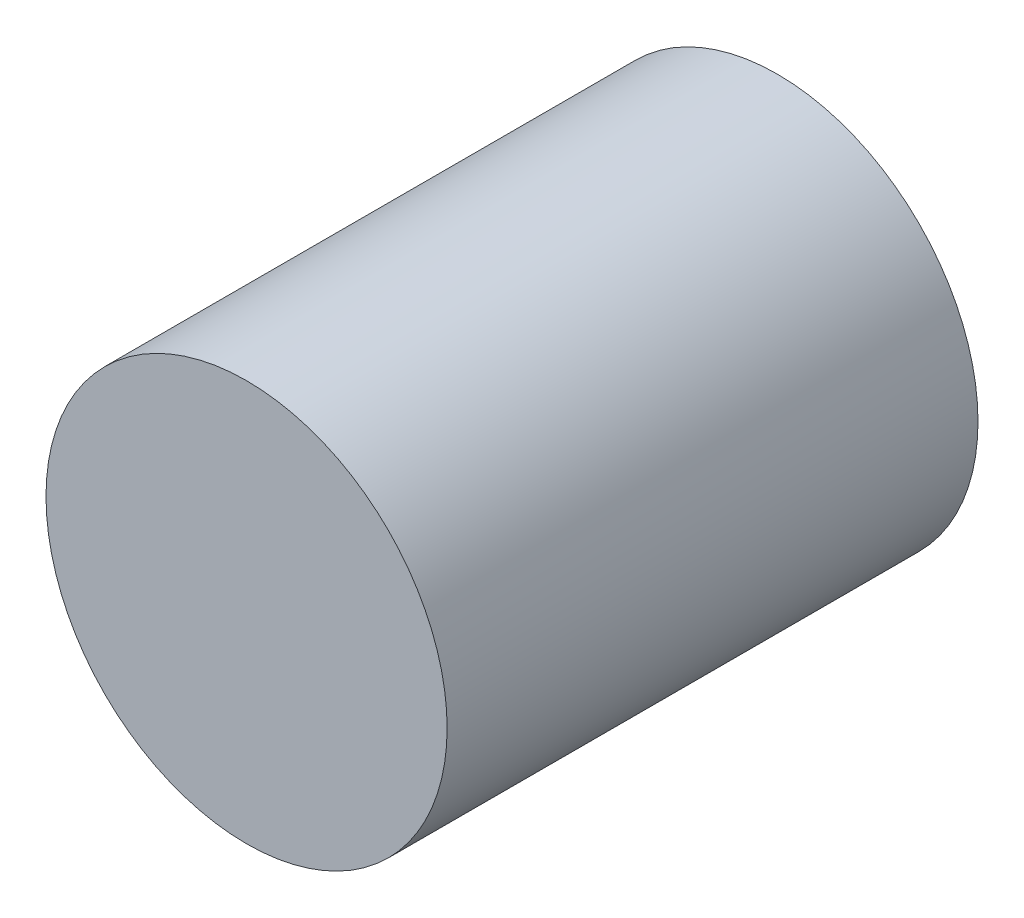
SolidWorks part; units mm, degrees
ref_plane "Front Plane" through (0, 0, 0) normal (0, 0, 1) x (1, 0, 0)
ref_plane "Top Plane" through (0, 0, 0) normal (0, 1, 0) x (1, 0, 0)
ref_plane "Right Plane" through (0, 0, 0) normal (1, 0, 0) x (0, 0, -1)
sketch "Sketch1" plane through (0, 0, 0) normal (0, 0, 1) x (1, 0, 0)
  circle A0 centre (0, 0) radius 37.7807
extrude "Boss-Extrude1" add sketch "Sketch1" along normal blind 100
